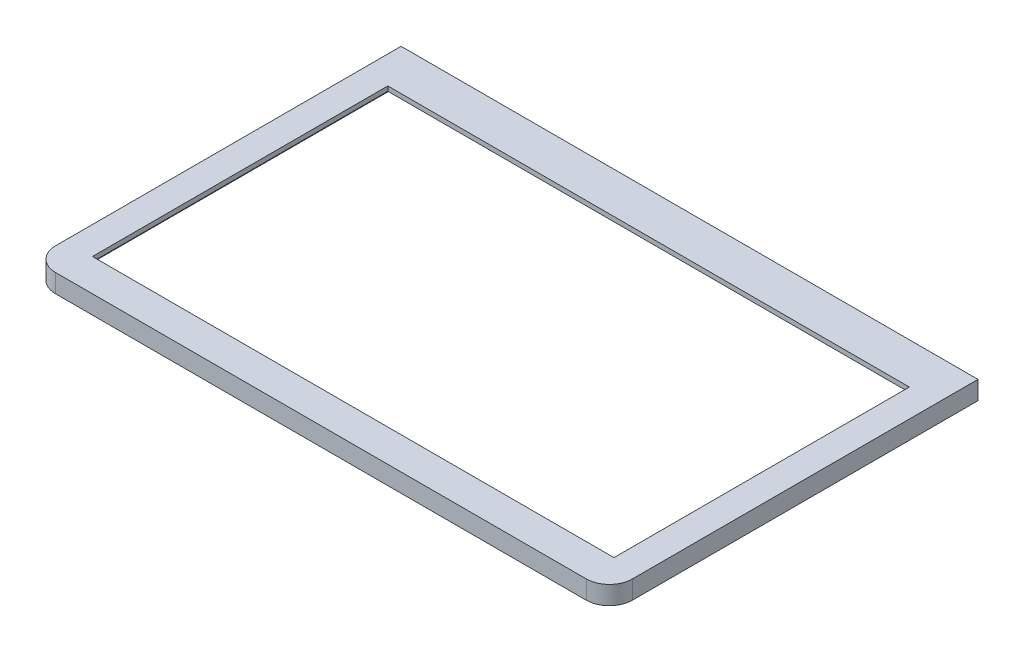
SolidWorks part; units mm, degrees
ref_plane "前视基准面" through (0, 0, 0) normal (0, 0, 1) x (1, 0, 0)
ref_plane "上视基准面" through (0, 0, 0) normal (0, 1, 0) x (1, 0, 0)
ref_plane "右视基准面" through (0, 0, 0) normal (1, 0, 0) x (0, 0, -1)
sketch "草图1" plane through (0, 0, 0) normal (0, 1, 0) x (1, 0, 0)
  line L1 (-99.3407, 63.102) -> (150.6593, 63.102)
  line L2 (-99.3407, 63.102) -> (-99.3407, -92.898)
  line L3 (-99.3407, -92.898) -> (150.6593, -92.898)
  line L4 (150.6593, 63.102) -> (150.6593, -92.898)
  line L5 (-87.3407, 49.102) -> (138.6593, 49.102)
  line L6 (-87.3407, 49.102) -> (-87.3407, -78.898)
  line L7 (-90.3407, 52.102) -> (143.6593, 52.102) construction
  line L8 (-90.3407, 52.102) -> (-90.3407, -85.898) construction
  line L9 (-90.3407, -85.898) -> (143.6593, -85.898) construction
  line L10 (143.6593, 52.102) -> (143.6593, -85.898) construction
  line L11 (-87.3407, -78.898) -> (138.6593, -78.898)
  line L12 (138.6593, 49.102) -> (138.6593, -78.898)
  point P4 (18.2503, -8.9096)
  point P9 (19.2503, -5.5256)
  point P14 (25.6593, -14.898)
  dimension "D1" = 250
  dimension "D2" = 156
  dimension "D3" = 138
  dimension "D4" = 234
  dimension "D5" = 9
  dimension "D6" = 7
  dimension "D7" = 11
  dimension "D8" = 7
  dimension "D9" = 3
  dimension "D10" = 3
  dimension "D11" = 7
  dimension "D12" = 5
extrude "凸台-拉伸1" add sketch "草图1" along normal blind 8
sketch "草图2" plane through (0, 0, 0) normal (0, -1, 0) x (1, 0, 0)
  line L0 (-99.3407, -63.102) -> (-99.3407, 92.898) construction
  line L1 (-93.0907, 82.648) -> (142.4093, 82.648)
  line L2 (-93.0907, 82.648) -> (-93.0907, -56.852)
  line L3 (-93.0907, -56.852) -> (142.4093, -56.852)
  line L4 (142.4093, 82.648) -> (142.4093, -56.852)
  line L5 (-93.0907, 82.648) -> (142.4093, -56.852) construction
  line L6 (-93.0907, -56.852) -> (142.4093, 82.648) construction
  line L7 (-99.3407, 92.898) -> (150.6593, 92.898) construction
  line L13 (150.6593, 92.898) -> (150.6593, -63.102) construction
  line L14 (150.6593, -63.102) -> (-99.3407, -63.102) construction
  point P4 (24.6593, 12.898)
  dimension "D1" = 235.5
  dimension "D2" = 139.5
  dimension "D3" = 6.25
  dimension "D4" = 10.25
  dimension "D5" = 8.25
  dimension "D6" = 6.25
extrude "切除-拉伸3" cut sketch "草图2" against normal blind 6
sketch "草图11" plane through (0, 0, -63.102) normal (0, 0, -1) x (-1, 0, 0)
  line L0 (99.3407, 8) -> (99.3407, 0) construction
  line L1 (-150.6593, 8) -> (99.3407, 8)
  line L2 (-150.6593, 8) -> (-150.6593, 0)
  line L3 (-150.6593, 0) -> (99.3407, 0)
  line L4 (99.3407, 8) -> (99.3407, 0)
  line L5 (-150.6593, 8) -> (99.3407, 0) construction
  line L6 (-150.6593, 0) -> (99.3407, 8) construction
  point P4 (-25.6593, 4)
extrude "凸台-拉伸3" add sketch "草图11" along normal blind 3.75
sketch "草图12" plane through (0, 8, 0) normal (0, 1, 0) x (1, 0, 0)
  line L0 (-99.3407, -82.898) -> (-99.3407, -92.898)
  line L3 (-89.3407, -92.898) -> (140.6593, -92.898) construction
  line L7 (-99.3407, -92.898) -> (-89.3407, -92.898)
  line L12 (150.6593, -82.898) -> (150.6593, -92.898)
  line L13 (150.6593, -92.898) -> (140.6593, -92.898)
  arc A1 (150.6593, -82.898) -> (140.6593, -92.898) centre (140.6593, -82.898) cw
  arc A2 (-89.3407, -92.898) -> (-99.3407, -82.898) centre (-89.3407, -82.898) cw
  point P4 (25.6593, -13.023)
  point P18 (0, 0)
extrude "切除-拉伸4" cut sketch "草图12" against normal blind 10
